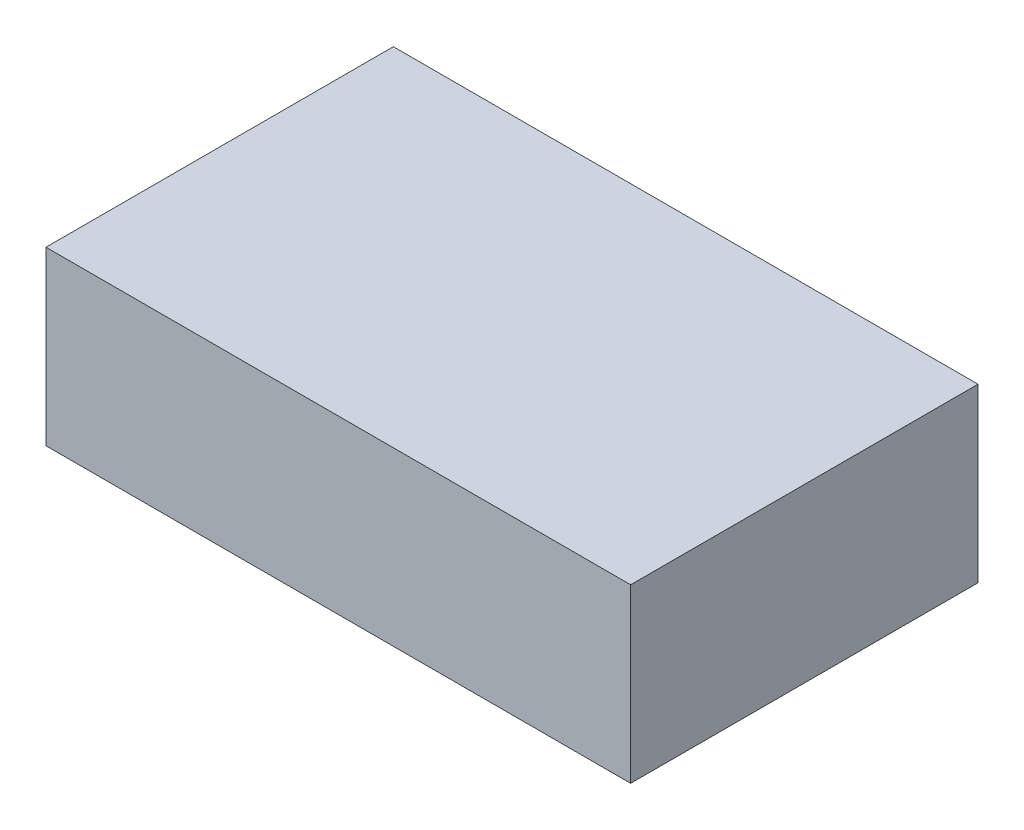
SolidWorks part; units mm, degrees
ref_plane "Front Plane" through (0, 0, 0) normal (0, 0, 1) x (1, 0, 0)
ref_plane "Top Plane" through (0, 0, 0) normal (0, 1, 0) x (1, 0, 0)
ref_plane "Right Plane" through (0, 0, 0) normal (1, 0, 0) x (0, 0, -1)
sketch "Sketch1" plane through (0, 0, 0) normal (0, 1, 0) x (1, 0, 0)
  line L1 (0, 0) -> (85, 0)
  line L2 (0, 0) -> (0, 50.5)
  line L3 (0, 50.5) -> (85, 50.5)
  line L4 (85, 0) -> (85, 50.5)
  dimension "D1" = 85
  dimension "D2" = 50.5
extrude "Boss-Extrude1" add sketch "Sketch1" along normal blind 25
